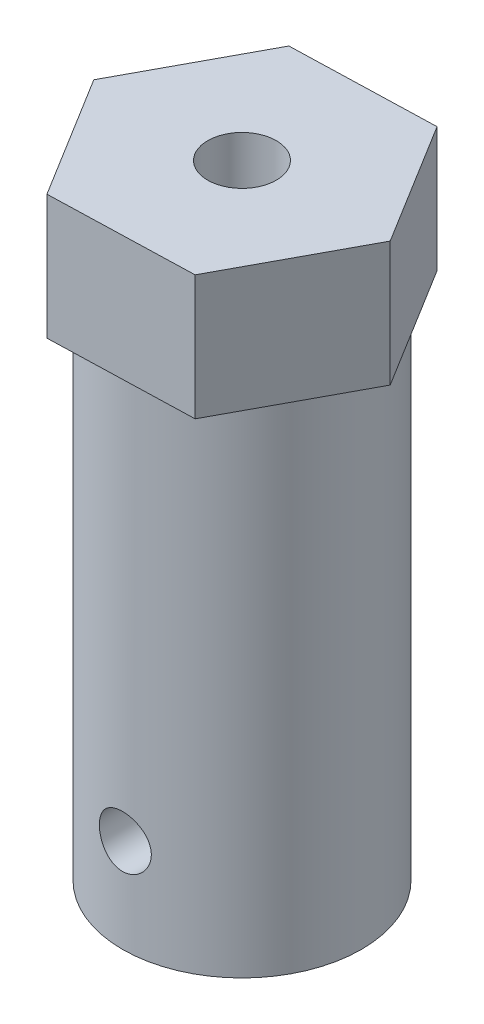
SolidWorks part; units mm, degrees
ref_plane "前视基准面" through (0, 0, 0) normal (0, 0, 1) x (1, 0, 0)
ref_plane "上视基准面" through (0, 0, 0) normal (0, 1, 0) x (1, 0, 0)
ref_plane "右视基准面" through (0, 0, 0) normal (1, 0, 0) x (0, 0, -1)
sketch "草图1" plane through (0, 0, 0) normal (0, 1, 0) x (1, 0, 0)
  circle A0 centre (0, 0) radius 3
  circle A1 centre (0, 0) radius 5.75
  dimension "D1" = 6
  dimension "D2" = 11.5
extrude "凸台-拉伸1" add sketch "草图1" along normal blind 24
ref_plane "基准面1" through (0, 0, 5.75) normal (0, 0, 1) x (1, 0, 0)
sketch "草图5" plane through (0, 0, 5.75) normal (0, 0, 1) x (1, 0, 0)
  line L0 (0, 0) -> (0, 4.5) construction
  dimension "D1" = 4.5
hole_wizard "M3 螺纹孔1" positions "草图7" profile "草图8" tap size "M3" standard "GB"
sketch "草图7" plane through (0, 0, 5.75) normal (0, 0, 1) x (1, 0, 0)
  point P0 (0, 4.5)
cosmetic thread "孔螺蚊线1" parameters "D1"=3.0228, "D2"=3
sketch "草图8" plane through (0, 4.5, 5.75) normal (1, 0, 0) x (0, -1, 0)
  line L0 (0, 0) -> (0, 8.5)
  line L1 (0, 8.5) -> (1.25, 7.7489)
  line L2 (1.25, 7.7489) -> (1.25, 0)
  line L5 (1.25, 0) -> (0, 0)
  line L10 (0, 8.5) -> (-1.25, 7.7489) construction
  line L11 (0, -6.35) -> (0, 107.95) construction
  dimension "螺纹孔钻头直径" = 2.5
  dimension "螺纹孔钻头深度" = 8.5
  dimension "导头角度" = 118
sketch "草图11" plane through (0, 24, 0) normal (0, 1, 0) x (1, 0, 0)
  line L1 (6.9252, 0.2046) -> (3.2854, 6.0997)
  line L2 (3.2854, 6.0997) -> (-3.6398, 5.8951)
  line L3 (-3.6398, 5.8951) -> (-6.9252, -0.2046)
  line L4 (-6.9252, -0.2046) -> (-3.2854, -6.0997)
  line L5 (-3.2854, -6.0997) -> (3.6398, -5.8951)
  line L6 (3.6398, -5.8951) -> (6.9252, 0.2046)
  circle A0 centre (0, 0) radius 6 construction
  dimension "D1" = 12
extrude "凸台-拉伸2" add sketch "草图11" along normal blind 6
hole_wizard "M4 螺纹孔的螺纹孔钻头1" positions "草图12" profile "草图14" hole size "M4" standard "GB" end condition through all
sketch "草图12" plane through (0, 30, 0) normal (0, 1, 0) x (1, 0, 0)
  point P0 (0, 0)
  point P4 (0, 0)
sketch "草图14" plane through (0, 30, 0) normal (1, 0, 0) x (0, 0, 1)
  line L0 (0, 0) -> (0, 30)
  line L1 (0, 30) -> (1.65, 30)
  line L2 (1.65, 30) -> (1.65, 0)
  line L5 (1.65, 0) -> (0, 0)
  line L11 (0, -6.35) -> (0, 107.95) construction
  dimension "通孔孔直径" = 3.3
  dimension "通孔孔深度" = 30
cosmetic thread "装饰螺纹线1" parameters "D2"=4
